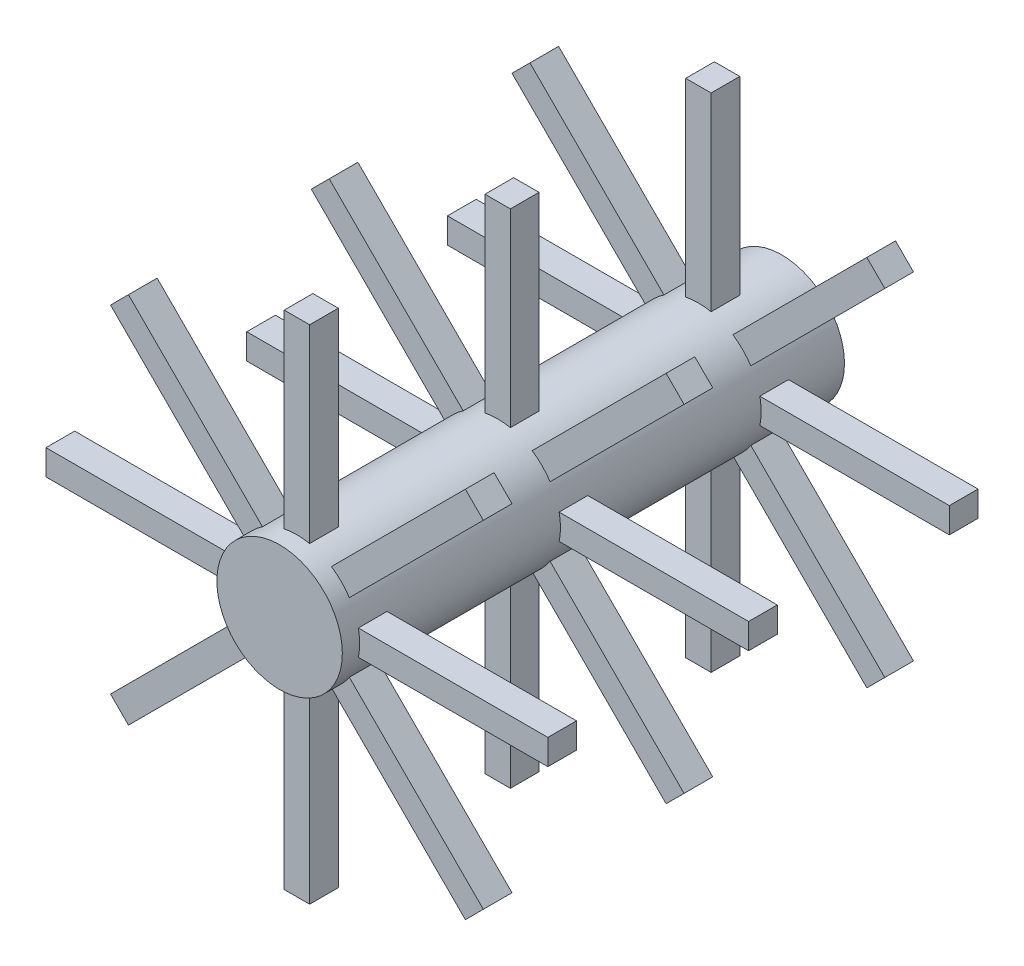
SolidWorks part; units mm, degrees
ref_plane "Front Plane" through (0, 0, 0) normal (0, 0, 1) x (1, 0, 0)
ref_plane "Top Plane" through (0, 0, 0) normal (0, 1, 0) x (1, 0, 0)
ref_plane "Right Plane" through (0, 0, 0) normal (1, 0, 0) x (0, 0, -1)
sketch "Sketch1" plane through (0, 0, 0) normal (0, 0, 1) x (1, 0, 0)
  circle A0 centre (0, 0) radius 25.4
  dimension "D1" = 50.8
extrude "Boss-Extrude1" add sketch "Sketch1" along normal blind 203.3151
sketch "Sketch3" plane through (0, 0, 0) normal (1, 0, 0) x (0, 0, -1)
  line L1 (-196.3087, -5.1404) -> (-184.6983, -5.1404)
  line L2 (-196.3087, -5.1404) -> (-196.3087, 5.1404)
  line L3 (-196.3087, 5.1404) -> (-184.6983, 5.1404)
  line L4 (-184.6983, -5.1404) -> (-184.6983, 5.1404)
  line L5 (-196.3087, -5.1404) -> (-184.6983, 5.1404) construction
  line L6 (-196.3087, 5.1404) -> (-184.6983, -5.1404) construction
  point P0 (-190.5035, 0)
extrude "Boss-Extrude3" add sketch "Sketch3" along normal blind 101.6
pattern_circular "CirPattern4" count 8 over 360 about axis through (0, 0, 0) along (0, 0, 1) of "Boss-Extrude3"
pattern_linear "LPattern1" count 3 spacing 81.28 along (0, 0, -1) of "CirPattern4", "Boss-Extrude3"
